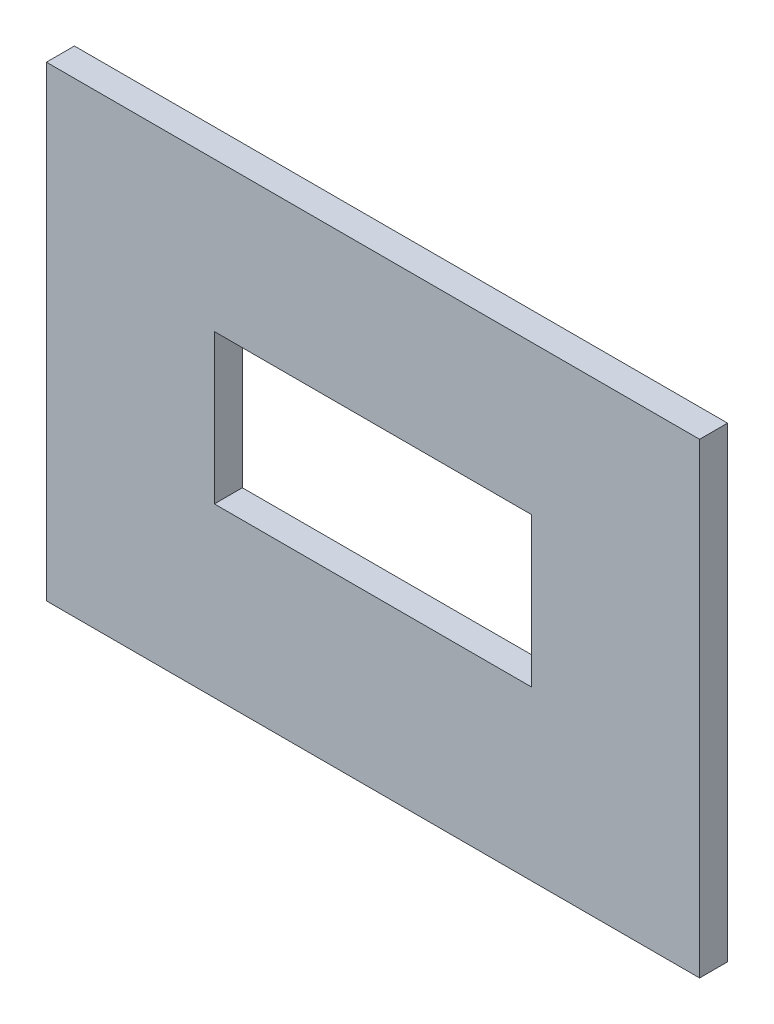
SolidWorks part; units mm, degrees
material "Thornel VCB-20 碳布"
ref_plane "前视基准面" through (0, 0, 0) normal (0, 0, 1) x (1, 0, 0)
ref_plane "上视基准面" through (0, 0, 0) normal (0, 1, 0) x (1, 0, 0)
ref_plane "右视基准面" through (0, 0, 0) normal (1, 0, 0) x (0, 0, -1)
other "Configuration Table"
sketch "草图1" plane through (0, 0, 0) normal (0, 0, 1) x (1, 0, 0)
  line L0 (0, 0) -> (0, 50)
  line L1 (0, 50) -> (70, 50)
  line L2 (70, 50) -> (70, 0)
  line L3 (70, 0) -> (54, 0)
  line L5 (52, 34) -> (18, 34)
  line L7 (16, 0) -> (0, 0)
  line L8 (18, 18) -> (52, 18)
  line L9 (16, 0) -> (54, 0)
  line L11 (18, 18) -> (18, 34)
  line L12 (52, 34) -> (52, 18)
  dimension "D1" = 16
  dimension "D2" = 16
  dimension "D3" = 34
  dimension "D4" = 16
  dimension "D5" = 50
  dimension "D6" = 18
  dimension "D7" = 18
  dimension "D8" = 18
extrude "凸台-拉伸2" add sketch "草图1" along normal blind 3
sketch "草图2" plane through (0, 0, 0) normal (0, 0, -1) x (-1, 0, 0)
  line L0 (-62, 8) -> (-8, 8) construction
  line L1 (-70, 0) -> (-70, 50) construction
  line L2 (0, 50) -> (0, 0) construction
  line L3 (0, 0) -> (-70, 0) construction
  line L4 (-44, 41) -> (-28, 41) construction
  line L6 (1526, 48) -> (-74, 48) construction
  circle A0 centre (-62, 8) radius 2.5
  circle A1 centre (-8, 8) radius 2.5
  circle A2 centre (-42, 8) radius 2.5
  circle A3 centre (-28, 8) radius 2.5
  circle A4 centre (-44, 41) radius 2.5
  circle A5 centre (-28, 41) radius 2.5
  dimension "D1" = 5
  dimension "D7" = 5
  dimension "D2" = 8
  dimension "D3" = 8
  dimension "D4" = 20
  dimension "D5" = 20
  dimension "D6" = 8
  dimension "D8" = 16
  dimension "D9" = 7
  dimension "D10" = 28
